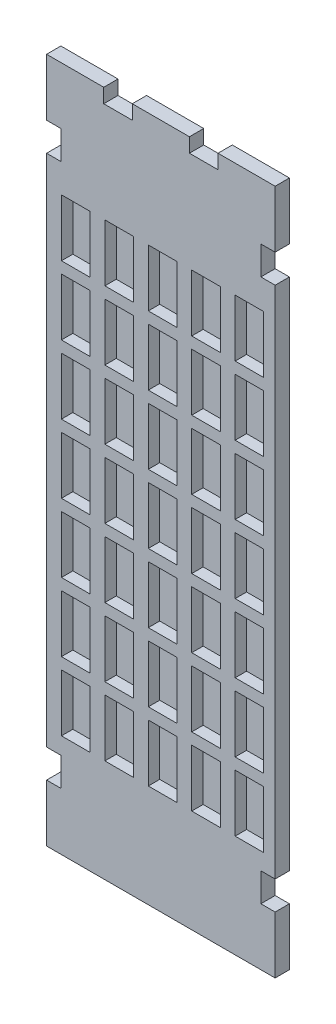
SolidWorks part; units mm, degrees
ref_plane "Front Plane" through (0, 0, 0) normal (0, 0, 1) x (1, 0, 0)
ref_plane "Top Plane" through (0, 0, 0) normal (0, 1, 0) x (1, 0, 0)
ref_plane "Right Plane" through (0, 0, 0) normal (1, 0, 0) x (0, 0, -1)
sketch "Sketch1" plane through (0, 0, 0) normal (0, 0, 1) x (1, 0, 0)
  line L0 (12.7, -152.4) -> (38.1, -152.4)
  line L1 (0, 0) -> (50.8, 0)
  line L2 (0, 0) -> (0, -152.4)
  line L3 (0, -152.4) -> (12.7, -152.4)
  line L4 (50.8, 0) -> (50.8, -152.4)
  line L5 (12.7, 0) -> (19.05, 0)
  line L6 (12.7, 0) -> (12.7, -3.175)
  line L7 (12.7, -3.175) -> (19.05, -3.175)
  line L8 (19.05, 0) -> (19.05, -3.175)
  line L9 (31.75, 0) -> (38.1, 0)
  line L10 (31.75, 0) -> (31.75, -3.175)
  line L11 (31.75, -3.175) -> (38.1, -3.175)
  line L12 (38.1, 0) -> (38.1, -3.175)
  line L13 (50.8, -12.7) -> (47.625, -12.7)
  line L14 (50.8, -12.7) -> (50.8, -19.05)
  line L15 (50.8, -19.05) -> (47.625, -19.05)
  line L16 (47.625, -12.7) -> (47.625, -19.05)
  line L17 (50.8, -133.35) -> (47.625, -133.35)
  line L18 (50.8, -133.35) -> (50.8, -139.7)
  line L19 (50.8, -139.7) -> (47.625, -139.7)
  line L20 (47.625, -133.35) -> (47.625, -139.7)
  line L25 (38.1, -152.4) -> (50.8, -152.4)
  line L29 (0, -139.7) -> (3.175, -139.7)
  line L30 (0, -139.7) -> (0, -133.35)
  line L31 (0, -133.35) -> (3.175, -133.35)
  line L32 (3.175, -139.7) -> (3.175, -133.35)
  line L33 (0, -19.05) -> (3.175, -19.05)
  line L34 (0, -19.05) -> (0, -12.7)
  line L35 (0, -12.7) -> (3.175, -12.7)
  line L36 (3.175, -19.05) -> (3.175, -12.7)
  dimension "D1" = 50.8
  dimension "D2" = 152.4
  dimension "D3" = 12.7
  dimension "D4" = 6.35
  dimension "D5" = 3.175
  dimension "D6" = 6.35
  dimension "D7" = 3.175
  dimension "D8" = 12.7
  dimension "D9" = 12.7
  dimension "D10" = 6.35
  dimension "D11" = 3.175
  dimension "D12" = 3.175
  dimension "D13" = 6.35
  dimension "D14" = 12.7
  dimension "D21" = 3.175
  dimension "D22" = 6.35
  dimension "D23" = 12.7
  dimension "D24" = 12.7
  dimension "D25" = 6.35
  dimension "D26" = 3.175
extrude "Boss-Extrude1" add sketch "Sketch1" along normal blind 3.175
sketch "Sketch2" plane through (0, 0, 3.175) normal (0, 0, 1) x (1, 0, 0)
  line L0 (0, -19.05) -> (0, -133.35) construction
  line L1 (3.302, -25.4) -> (9.652, -25.4)
  line L2 (3.302, -25.4) -> (3.302, -38.1)
  line L3 (3.302, -38.1) -> (9.652, -38.1)
  line L4 (9.652, -25.4) -> (9.652, -38.1)
  line L5 (3.302, -25.4) -> (9.652, -38.1) construction
  line L6 (3.302, -38.1) -> (9.652, -25.4) construction
  line L7 (0, -19.05) -> (3.175, -19.05) construction
  point P0 (6.477, -31.75)
  dimension "D1" = 6.35
  dimension "D2" = 12.7
  dimension "D3" = 3.302
  dimension "D4" = 6.35
extrude "Cut-Extrude1" cut sketch "Sketch2" against normal blind 2.54
pattern_linear "LPattern1" count 5 spacing 9.652 along (1, 0, 0) count 7 spacing 15.24 along (0, -1, 0) of "Cut-Extrude1"
